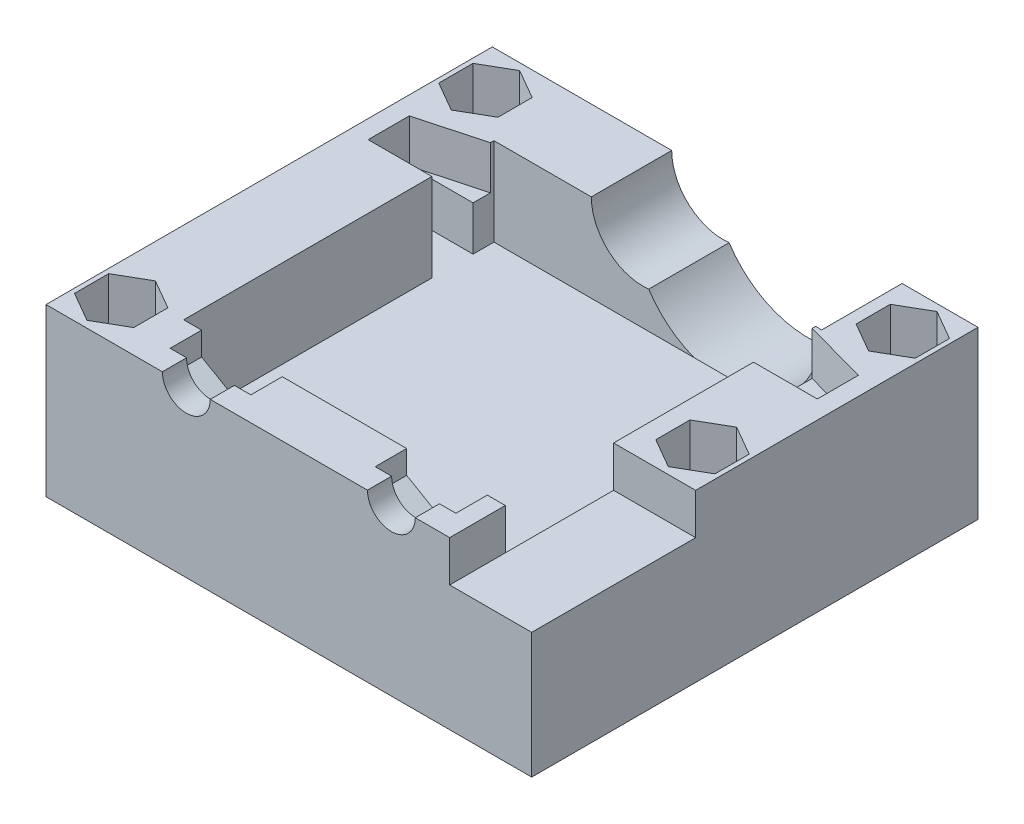
SolidWorks part; units mm, degrees
material "PLA"
ref_plane "Front Plane" through (0, 0, 0) normal (0, 0, 1) x (1, 0, 0)
ref_plane "Top Plane" through (0, 0, 0) normal (0, 1, 0) x (1, 0, 0)
ref_plane "Right Plane" through (0, 0, 0) normal (1, 0, 0) x (0, 0, -1)
sketch "Sketch1" plane through (0, 0, 0) normal (0, 1, 0) x (1, 0, 0)
  line L1 (-17.76, -16.3195) -> (17.76, -16.3195)
  line L2 (-17.76, -16.3195) -> (-17.76, 16.3195)
  line L3 (-17.76, 16.3195) -> (17.76, 16.3195)
  line L4 (17.76, -16.3195) -> (17.76, 16.3195)
  line L5 (-17.76, -16.3195) -> (17.76, 16.3195) construction
  line L6 (-17.76, 16.3195) -> (17.76, -16.3195) construction
  point P0 (0, 0)
  dimension "D1" = 35.52
  dimension "D2" = 32.639
extrude "Boss-Extrude1" add sketch "Sketch1" along normal blind 12.17
sketch "Sketch2" plane through (0, 12.17, 0) normal (0, 1, 0) x (1, 0, 0)
  line L0 (-17.76, -16.3195) -> (-17.76, -15.8195) construction
  line L1 (-17.76, 16.3195) -> (-17.76, -16.3195) construction
  line L2 (-17.76, -15.8195) -> (-15.26, -15.8195) construction
  line L3 (-15.26, -15.8195) -> (-15.26, -10.8195) construction
  line L4 (-6.6935, 0) -> (6.6935, 0) construction
  line L5 (-15.26, -10.8195) -> (-17.4251, -12.0695)
  line L6 (-17.4251, -12.0695) -> (-17.4251, -14.5695)
  line L7 (-17.4251, -14.5695) -> (-15.26, -15.8195)
  line L8 (-15.26, -15.8195) -> (-13.0949, -14.5695)
  line L9 (-13.0949, -14.5695) -> (-13.0949, -12.0695)
  line L10 (-13.0949, -12.0695) -> (-15.26, -10.8195)
  line L11 (-15.26, 15.8195) -> (-15.26, 10.8195) construction
  line L12 (-17.76, 15.8195) -> (-15.26, 15.8195) construction
  line L13 (-13.0949, 12.0695) -> (-15.26, 10.8195)
  line L14 (-13.0949, 14.5695) -> (-13.0949, 12.0695)
  line L15 (-15.26, 15.8195) -> (-13.0949, 14.5695)
  line L16 (-17.4251, 14.5695) -> (-15.26, 15.8195)
  line L17 (-15.26, 10.8195) -> (-17.4251, 12.0695)
  line L18 (-17.4251, 12.0695) -> (-17.4251, 14.5695)
  line L19 (0, -6.6935) -> (0, 6.6935) construction
  line L20 (17.76, 15.8195) -> (15.26, 15.8195) construction
  line L21 (15.26, 15.8195) -> (15.26, 10.8195) construction
  line L22 (17.4251, 12.0695) -> (17.4251, 14.5695)
  line L23 (15.26, 10.8195) -> (17.4251, 12.0695)
  line L24 (17.4251, 14.5695) -> (15.26, 15.8195)
  line L25 (15.26, 15.8195) -> (13.0949, 14.5695)
  line L26 (13.0949, 14.5695) -> (13.0949, 12.0695)
  line L27 (13.0949, 12.0695) -> (15.26, 10.8195)
  line L28 (15.26, 10.8195) -> (15.26, 1.1695) construction
  line L29 (15.26, 1.1695) -> (15.26, -3.8305) construction
  line L31 (15.26, 1.1695) -> (13.0949, -0.0805)
  line L32 (13.0949, -0.0805) -> (13.0949, -2.5805)
  line L33 (13.0949, -2.5805) -> (15.26, -3.8305)
  line L34 (15.26, -3.8305) -> (17.4251, -2.5805)
  line L35 (17.4251, -2.5805) -> (17.4251, -0.0805)
  line L36 (17.4251, -0.0805) -> (15.26, 1.1695)
  circle A0 centre (-15.26, -13.3195) radius 2.1651 construction
  circle A1 centre (-15.26, 13.3195) radius 2.1651 construction
  circle A2 centre (15.26, 13.3195) radius 2.1651 construction
  circle A3 centre (15.26, -1.3305) radius 2.1651 construction
  dimension "D1" = 0.5
  dimension "D2" = 2.5
  dimension "D3" = 5
  dimension "D4" = 9.65
  dimension "D5" = 5
extrude "Cut-Extrude1" cut sketch "Sketch2" against normal blind 5.25
sketch "Sketch3" plane through (0, 12.17, 0) normal (0, 1, 0) x (1, 0, 0)
  line L0 (0, -6.6935) -> (0, 6.6935) construction
  line L1 (-6.6935, 0) -> (6.6935, 0) construction
  circle A0 centre (-15.26, 13.3195) radius 1.25
  circle A1 centre (15.26, 13.3195) radius 1.25
  circle A2 centre (-15.26, -13.3195) radius 1.25
  circle A3 centre (15.26, -1.3305) radius 1.25
  dimension "D1" = 2.5
extrude "Cut-Extrude2" cut sketch "Sketch3" against normal through all
sketch "Sketch4" plane through (0, 12.17, 0) normal (0, 1, 0) x (1, 0, 0)
  line L1 (17.76, -16.3195) -> (11.76, -16.3195)
  line L2 (17.76, -16.3195) -> (17.76, -4.3307)
  line L3 (17.76, -4.3307) -> (11.76, -4.3307)
  line L4 (11.76, -16.3195) -> (11.76, -4.3307)
  dimension "D1" = 6
  dimension "D2" = 11.9888
extrude "Cut-Extrude3" cut sketch "Sketch4" against normal blind 3
sketch "Sketch5" plane through (0, 12.17, 0) normal (0, 1, 0) x (1, 0, 0)
  line L0 (17.76, -16.3195) -> (11.7656, -16.3195) construction
  line L2 (11.7656, -16.3195) -> (11.76, -12.2495) construction
  line L3 (11.76, -16.3195) -> (17.76, -16.3195) construction
  line L4 (-11.76, -12.2495) -> (11.76, -12.2495)
  line L5 (-11.76, -12.2495) -> (-11.76, 10.4405)
  line L6 (-11.76, 10.4405) -> (11.76, 10.4405)
  line L7 (11.76, -12.2495) -> (11.76, 10.4405)
  line L8 (11.76, -4.3307) -> (11.76, -16.3195) construction
  dimension "D1" = 5.9944
  dimension "D2" = 4.07
  dimension "D3" = 22.69
  dimension "D4" = 23.52
extrude "Cut-Extrude4" cut sketch "Sketch5" against normal blind 6.425
sketch "Sketch6" plane through (0, 0, 16.3195) normal (0, 0, 1) x (1, 0, 0)
  line L0 (-17.76, 12.17) -> (-9.25, 12.17) construction
  line L1 (-17.76, 12.17) -> (11.76, 12.17) construction
  line L2 (-9.25, 12.17) -> (-5.75, 12.17) construction
  line L3 (-5.75, 12.17) -> (5.746, 12.17) construction
  line L4 (5.746, 12.17) -> (9.246, 12.17) construction
  line L5 (-7.5, 12.17) -> (7.496, 12.17) construction
  circle A0 centre (-7.5, 12.17) radius 1.75
  circle A1 centre (7.496, 12.17) radius 1.75
  dimension "D1" = 8.51
  dimension "D2" = 3.5
  dimension "D3" = 14.996
  dimension "D4" = 3.5
extrude "Cut-Extrude5" cut sketch "Sketch6" against normal up to surface (4.07 mm away) up to face at (2.352, 9, 12.2495)
sketch "Sketch7" plane through (0, 0, 12.2495) normal (0, 0, -1) x (-1, 0, 0)
  line L0 (9.25, 12.17) -> (5.75, 12.17) construction
  line L1 (-5.746, 12.17) -> (-9.246, 12.17) construction
  line L2 (9.25, 12.17) -> (5.75, 12.17) construction
  line L3 (-5.746, 12.17) -> (-9.246, 12.17) construction
  line L4 (-7.496, 12.17) -> (-7.496, 8.7636) construction
  line L5 (7.5, 12.17) -> (7.5, 8.7636) construction
  line L7 (-7.496, 8.7636) -> (-4.546, 10.4668)
  line L8 (-4.546, 10.4668) -> (-4.546, 13.8732)
  line L9 (-4.546, 13.8732) -> (-7.496, 15.5764)
  line L10 (-7.496, 15.5764) -> (-10.446, 13.8732)
  line L11 (-10.446, 13.8732) -> (-10.446, 10.4668)
  line L12 (-10.446, 10.4668) -> (-7.496, 8.7636)
  line L13 (7.5, 8.7636) -> (10.45, 10.4668)
  line L14 (10.45, 10.4668) -> (10.45, 13.8732)
  line L15 (10.45, 13.8732) -> (7.5, 15.5764)
  line L16 (7.5, 15.5764) -> (4.55, 13.8732)
  line L17 (4.55, 13.8732) -> (4.55, 10.4668)
  line L18 (4.55, 10.4668) -> (7.5, 8.7636)
  circle A0 centre (-7.496, 12.17) radius 2.95 construction
  circle A1 centre (7.5, 12.17) radius 2.95 construction
extrude "Cut-Extrude6" cut sketch "Sketch7" against normal blind 2.3
sketch "Sketch8" plane through (0, 12.17, 0) normal (0, 1, 0) x (1, 0, 0)
  line L0 (17.76, 16.3195) -> (11.76, 16.3195) construction
  line L1 (17.76, 16.3195) -> (-17.76, 16.3195) construction
  line L2 (11.76, 16.3195) -> (11.76, 10.1835) construction
  line L3 (11.76, -4.3307) -> (11.76, 10.4405) construction
  line L4 (11.76, 10.1835) -> (16.425, 10.1835) construction
  line L5 (16.425, 10.1835) -> (16.425, 8.9135) construction
  line L6 (11.76, 10.1835) -> (16.425, 8.9135)
  line L7 (16.425, 8.9135) -> (11.76, 8.9135)
  line L8 (11.76, -12.2495) -> (11.76, 10.4405) construction
  line L9 (11.76, 8.9135) -> (11.76, 10.1835)
  line L14 (0, 10.4405) -> (0, -3.2846) construction
  line L15 (11.76, 10.4405) -> (-11.76, 10.4405) construction
  line L16 (-11.76, 10.1835) -> (-16.425, 10.1835) construction
  line L17 (-11.76, 16.3195) -> (-11.76, 10.1835) construction
  line L18 (-11.76, 8.9135) -> (-11.76, 10.1835)
  line L19 (-16.425, 8.9135) -> (-11.76, 8.9135)
  line L20 (-11.76, 10.1835) -> (-16.425, 8.9135)
  dimension "D1" = 6.136
  dimension "D2" = 1.27
  dimension "D3" = 4.665
extrude "Cut-Extrude7" cut sketch "Sketch8" against normal blind 3.175
sketch "Sketch9" plane through (0, 12.17, 0) normal (0, 1, 0) x (1, 0, 0)
  line L0 (0, 10.4405) -> (0, -4.3046) construction
  line L9 (11.76, 10.4405) -> (-11.76, 10.4405) construction
  line L10 (-16.4249, 8.9135) -> (-16.4249, 5.9035)
  line L11 (-11.76, 5.9035) -> (-16.4249, 5.9035)
  line L12 (-11.76, 8.9135) -> (-11.76, 5.9035)
  line L13 (-11.76, 8.9135) -> (-16.4249, 8.9135)
  line L15 (11.76, 8.9135) -> (16.425, 8.9135)
  line L16 (11.76, 8.9135) -> (11.76, 5.9035)
  line L17 (11.76, 5.9035) -> (16.425, 5.9035)
  line L18 (16.425, 8.9135) -> (16.425, 5.9035)
  dimension "D2" = 3.01
extrude "Cut-Extrude8" cut sketch "Sketch9" against normal up to surface (6.425 mm away) up to face at (0, 5.745, 0.9045)
sketch "Sketch10" plane through (0, 0, -16.3195) normal (0, 0, -1) x (-1, 0, 0)
  line L0 (-17.76, 12.17) -> (-12.21, 12.17) construction
  line L1 (-17.76, 12.17) -> (17.76, 12.17) construction
  line L2 (-12.21, 12.17) -> (4.64, 12.17)
  line L3 (4.55, 12.17) -> (4.55, 8.4357) construction
  line L4 (4.55, 8.4357) -> (0.4569, 8.4357) construction
  line L5 (4.55, 12.17) -> (2.8784, 12.17) construction
  line L6 (2.8784, 12.17) -> (2.8784, 8.9906) construction
  line L7 (0.4569, 8.4357) -> (0.4569, 5.2732) construction
  line L8 (0.4569, 5.2732) -> (-4.7504, 5.2732) construction
  line L9 (-12.21, 12.17) -> (-5.3315, 12.17) construction
  line L10 (4.64, 12.17) -> (0.8734, 12.17) construction
  arc A1 (-12.21, 12.17) -> (0.4404, 8.4284) centre (-5.3315, 12.17) ccw
  arc A4 (0.4404, 8.4284) -> (4.64, 12.17) centre (0.8734, 12.17) ccw
  dimension "D1" = 5.55
  dimension "D2" = 16.85
  dimension "D3" = 4.0931
  dimension "D4" = 3.7343
  dimension "D5" = 1.7616
  dimension "D6" = 3.1794
  dimension "D7" = 3.1625
  dimension "D8" = 5.2073
extrude "Cut-Extrude9" cut sketch "Sketch10" against normal up to surface (5.879 mm away) up to face at (0, 8.9575, -10.4405)
